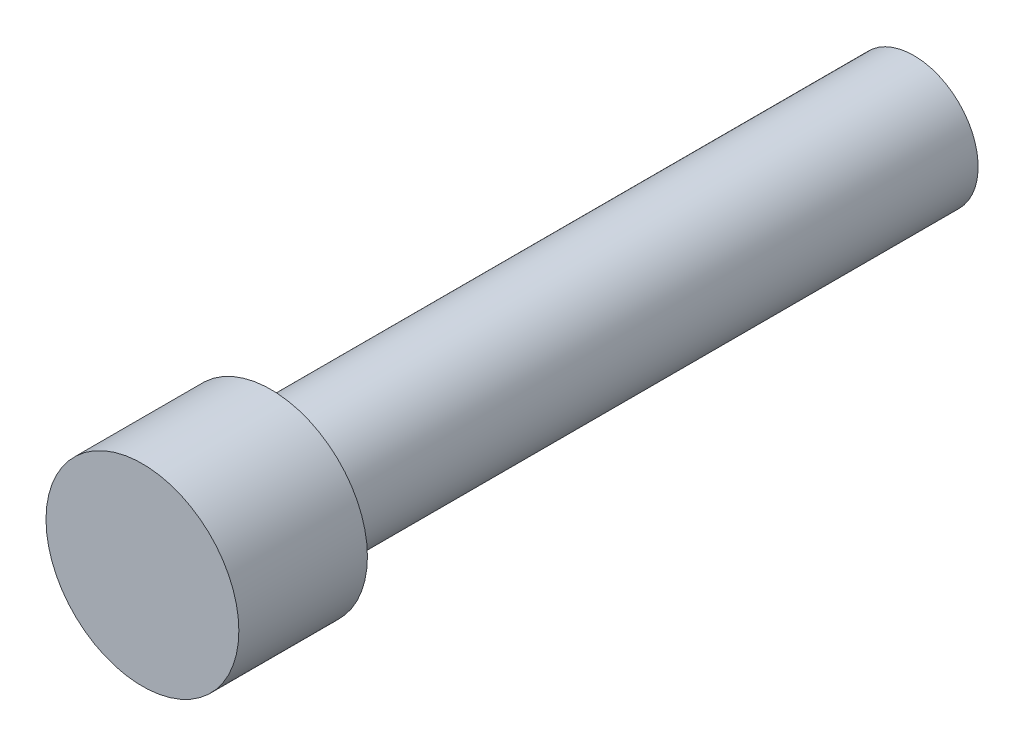
SolidWorks part; units mm, degrees
ref_plane "前视基准面" through (0, 0, 0) normal (0, 0, 1) x (1, 0, 0)
ref_plane "上视基准面" through (0, 0, 0) normal (0, 1, 0) x (1, 0, 0)
ref_plane "右视基准面" through (0, 0, 0) normal (1, 0, 0) x (0, 0, -1)
sketch "草图1" plane through (0, 0, 0) normal (0, 0, 1) x (1, 0, 0)
  circle A0 centre (0, 0) radius 1.5
  dimension "D1" = 3
extrude "凸台-拉伸1" add sketch "草图1" along normal blind 2
sketch "草图2" plane through (0, 0, 0) normal (0, 0, -1) x (-1, 0, 0)
  circle A0 centre (0, 0) radius 1
  dimension "D1" = 2
extrude "凸台-拉伸3" add sketch "草图2" along normal blind 10
